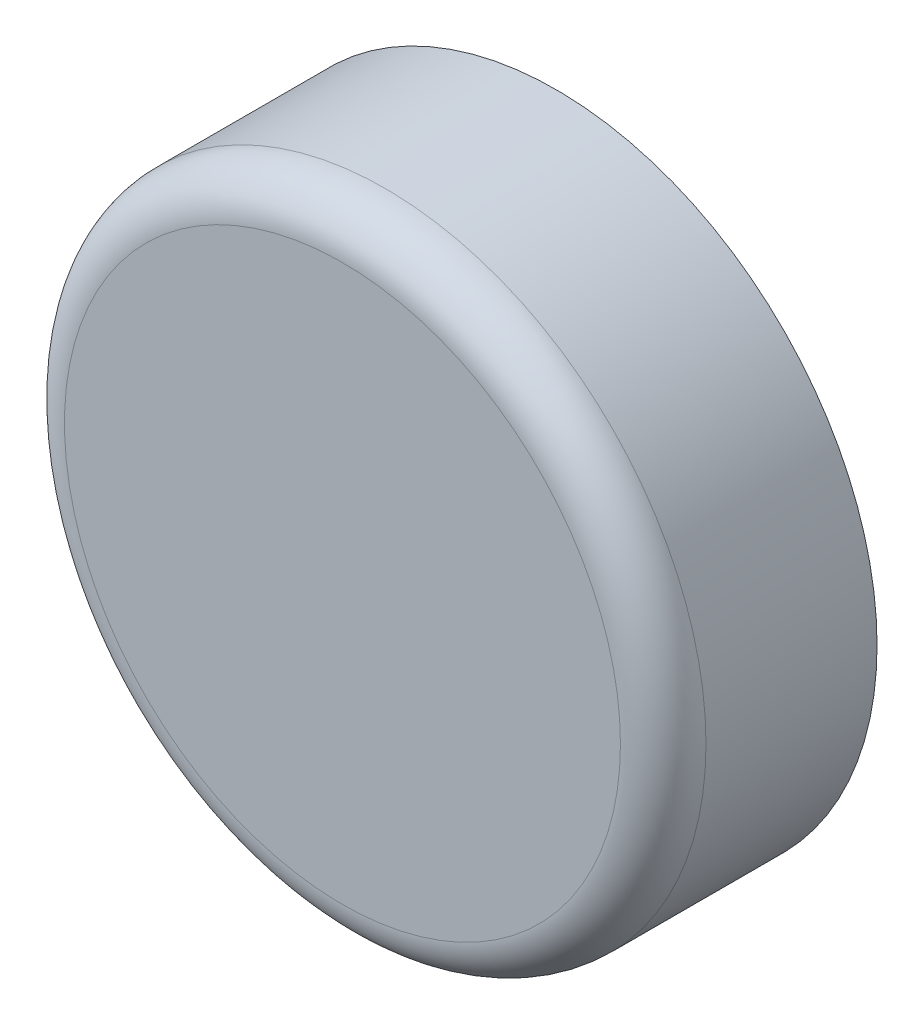
SolidWorks part; units mm, degrees
material "Glas"
ref_plane "Ebene vorne" through (0, 0, 0) normal (0, 0, 1) x (1, 0, 0)
ref_plane "Ebene oben" through (0, 0, 0) normal (0, 1, 0) x (1, 0, 0)
ref_plane "Ebene rechts" through (0, 0, 0) normal (1, 0, 0) x (0, 0, -1)
sketch "Skizze1" plane through (0, 0, 0) normal (0, 0, 1) x (1, 0, 0)
  circle A0 centre (0, 0) radius 15
  dimension "D1" = 30
extrude "Aufsatz-Linear austragen1" add sketch "Skizze1" along normal blind 10
fillet "Verrundung1" radius 2 1 edges at (15, 0, 10)
